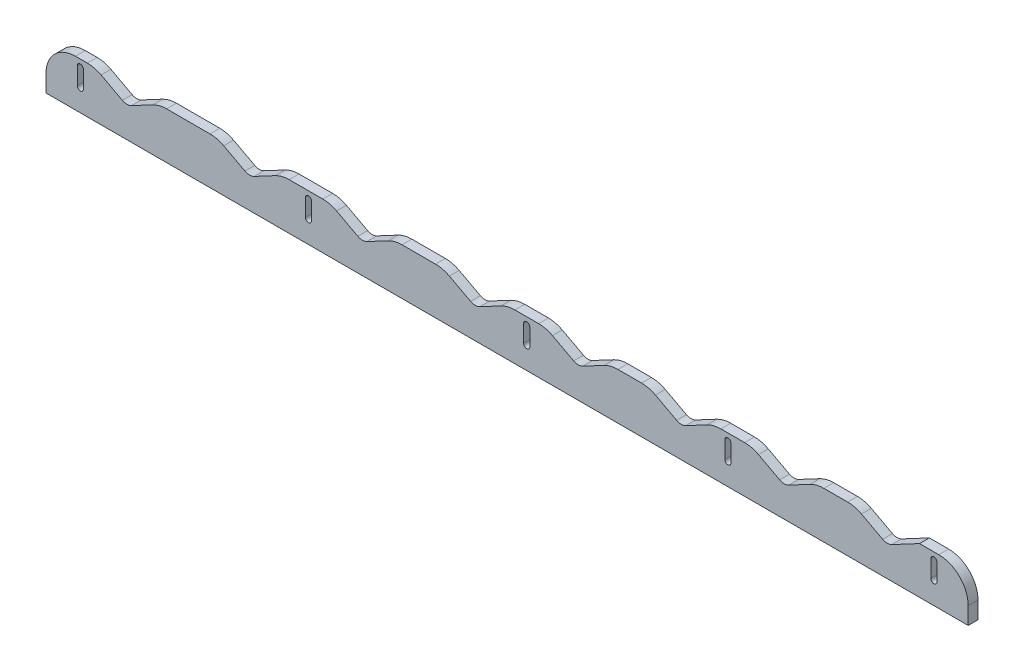
SolidWorks part; units mm, degrees
ref_plane "Plano frontal" through (0, 0, 0) normal (0, 0, 1) x (1, 0, 0)
ref_plane "Plano superior" through (0, 0, 0) normal (0, 1, 0) x (1, 0, 0)
ref_plane "Plano direito" through (0, 0, 0) normal (1, 0, 0) x (0, 0, -1)
sketch "Esboço1" plane through (0, 0, 0) normal (0, 0, 1) x (1, 0, 0)
  line L0 (-938.8238, -32.4718) -> (-936.8238, -32.4718)
  line L1 (-862.5738, 17.5282) -> (-862.5738, -17.4718)
  line L2 (-875.0738, -17.4718) -> (-875.0738, 17.5282)
  line L3 (-397.5738, 17.5282) -> (-397.5738, -17.4718)
  line L4 (-410.0738, -17.4718) -> (-410.0738, 17.5282)
  line L5 (34.9262, -17.4718) -> (34.9262, 17.5282)
  line L6 (47.4262, 17.5282) -> (47.4262, -17.4718)
  line L7 (457.4262, 17.5282) -> (457.4262, -17.4718)
  line L8 (444.9262, -17.4718) -> (444.9262, 17.5282)
  line L9 (864.9262, -17.4718) -> (864.9262, 17.5282)
  line L10 (877.4262, 17.5282) -> (877.4262, -17.4718)
  line L11 (941.1762, -32.4718) -> (941.1762, -27.4718)
  line L12 (881.1762, 32.5282) -> (846.2617, 32.5282)
  line L13 (846.2617, 32.5282) -> (842.0016, 32.5282)
  line L14 (842.0016, 32.5282) -> (785.5656, 2.5206)
  line L15 (766.7867, 2.5206) -> (723.5594, 25.505)
  line L16 (695.3911, 32.5282) -> (646.9613, 32.5282)
  line L17 (618.793, 25.505) -> (575.5656, 2.5206)
  line L18 (556.7867, 2.5206) -> (513.5594, 25.505)
  line L19 (485.3911, 32.5282) -> (436.9613, 32.5282)
  line L20 (408.793, 25.505) -> (365.5656, 2.5206)
  line L21 (346.7867, 2.5206) -> (303.5594, 25.505)
  line L22 (275.3911, 32.5282) -> (226.9613, 32.5282)
  line L23 (198.793, 25.505) -> (155.5656, 2.5206)
  line L24 (136.7867, 2.5206) -> (93.5594, 25.505)
  line L25 (65.3911, 32.5282) -> (16.9613, 32.5282)
  line L26 (-11.207, 25.505) -> (-54.4344, 2.5206)
  line L27 (-73.2133, 2.5206) -> (-116.4406, 25.505)
  line L28 (-144.6089, 32.5282) -> (-213.0387, 32.5282)
  line L29 (-241.207, 25.505) -> (-284.4344, 2.5206)
  line L30 (-303.2133, 2.5206) -> (-346.4406, 25.505)
  line L31 (-374.6089, 32.5282) -> (-443.0387, 32.5282)
  line L32 (-471.207, 25.505) -> (-514.4344, 2.5206)
  line L33 (-533.2133, 2.5206) -> (-576.4406, 25.505)
  line L34 (-604.6089, 32.5282) -> (-693.0387, 32.5282)
  line L35 (-721.207, 25.505) -> (-764.4344, 2.5206)
  line L36 (-783.2133, 2.5206) -> (-826.4406, 25.505)
  line L37 (-854.6089, 32.5282) -> (-878.8238, 32.5282)
  line L38 (-936.8238, -32.4718) -> (941.1762, -32.4718) construction
  line L39 (-938.8238, -27.4718) -> (-938.8238, -32.4718)
  line L40 (-938.8238, -32.4718) -> (-938.8238, -62.4718)
  line L41 (-938.8238, -62.4718) -> (941.1762, -62.4718)
  line L42 (941.1762, -62.4718) -> (941.1762, -32.4718)
  arc A0 (-862.5738, 17.5282) -> (-875.0738, 17.5282) centre (-868.8238, 17.5282) ccw
  arc A1 (-875.0738, -17.4718) -> (-862.5738, -17.4718) centre (-868.8238, -17.4718) ccw
  arc A2 (-410.0738, -17.4718) -> (-397.5738, -17.4718) centre (-403.8238, -17.4718) ccw
  arc A3 (-397.5738, 17.5282) -> (-410.0738, 17.5282) centre (-403.8238, 17.5282) ccw
  arc A4 (34.9262, -17.4718) -> (47.4262, -17.4718) centre (41.1762, -17.4718) ccw
  arc A5 (47.4262, 17.5282) -> (34.9262, 17.5282) centre (41.1762, 17.5282) ccw
  arc A6 (444.9262, -17.4718) -> (457.4262, -17.4718) centre (451.1762, -17.4718) ccw
  arc A7 (457.4262, 17.5282) -> (444.9262, 17.5282) centre (451.1762, 17.5282) ccw
  arc A8 (877.4262, 17.5282) -> (864.9262, 17.5282) centre (871.1762, 17.5282) ccw
  arc A9 (864.9262, -17.4718) -> (877.4262, -17.4718) centre (871.1762, -17.4718) ccw
  arc A10 (941.1762, -27.4718) -> (881.1762, 32.5282) centre (881.1762, -27.4718) ccw
  arc A11 (766.7867, 2.5206) -> (785.5656, 2.5206) centre (776.1762, 20.1796) ccw
  arc A12 (723.5594, 25.505) -> (695.3911, 32.5282) centre (695.3911, -27.4718) ccw
  arc A13 (646.9613, 32.5282) -> (618.793, 25.505) centre (646.9613, -27.4718) ccw
  arc A14 (556.7867, 2.5206) -> (575.5656, 2.5206) centre (566.1762, 20.1796) ccw
  arc A15 (513.5594, 25.505) -> (485.3911, 32.5282) centre (485.3911, -27.4718) ccw
  arc A16 (436.9613, 32.5282) -> (408.793, 25.505) centre (436.9613, -27.4718) ccw
  arc A17 (346.7867, 2.5206) -> (365.5656, 2.5206) centre (356.1762, 20.1796) ccw
  arc A18 (303.5594, 25.505) -> (275.3911, 32.5282) centre (275.3911, -27.4718) ccw
  arc A19 (226.9613, 32.5282) -> (198.793, 25.505) centre (226.9613, -27.4718) ccw
  arc A20 (136.7867, 2.5206) -> (155.5656, 2.5206) centre (146.1762, 20.1796) ccw
  arc A21 (93.5594, 25.505) -> (65.3911, 32.5282) centre (65.3911, -27.4718) ccw
  arc A22 (16.9613, 32.5282) -> (-11.207, 25.505) centre (16.9613, -27.4718) ccw
  arc A23 (-73.2133, 2.5206) -> (-54.4344, 2.5206) centre (-63.8238, 20.1796) ccw
  arc A24 (-116.4406, 25.505) -> (-144.6089, 32.5282) centre (-144.6089, -27.4718) ccw
  arc A25 (-213.0387, 32.5282) -> (-241.207, 25.505) centre (-213.0387, -27.4718) ccw
  arc A26 (-303.2133, 2.5206) -> (-284.4344, 2.5206) centre (-293.8238, 20.1796) ccw
  arc A27 (-346.4406, 25.505) -> (-374.6089, 32.5282) centre (-374.6089, -27.4718) ccw
  arc A28 (-443.0387, 32.5282) -> (-471.207, 25.505) centre (-443.0387, -27.4718) ccw
  arc A29 (-533.2133, 2.5206) -> (-514.4344, 2.5206) centre (-523.8238, 20.1796) ccw
  arc A30 (-576.4406, 25.505) -> (-604.6089, 32.5282) centre (-604.6089, -27.4718) ccw
  arc A31 (-693.0387, 32.5282) -> (-721.207, 25.505) centre (-693.0387, -27.4718) ccw
  arc A32 (-783.2133, 2.5206) -> (-764.4344, 2.5206) centre (-773.8238, 20.1796) ccw
  arc A33 (-826.4406, 25.505) -> (-854.6089, 32.5282) centre (-854.6089, -27.4718) ccw
  arc A34 (-878.8238, 32.5282) -> (-938.8238, -27.4718) centre (-878.8238, -27.4718) ccw
  dimension "D1" = 65
  dimension "D2" = 30
  dimension "D3" = 1880
extrude "Ressalto-extrusão1" add sketch "Esboço1" along normal blind 20 contours L0 L38 L11 A10 L12 L13 L14 A11 L15 A12 L16 A13 L17 A14 L18 A15 L19 A16 L20 A17 L21 A18 L22 A19 L23 A20 L24 A21 L25 A22 L26 A23 L27 A24 L28 A25 L29 A26 L30 A27 L31 A28 L32 A29 L33 A30 L34 A31 L35 A32 L36 | L38 L0 L40 L41 L42
